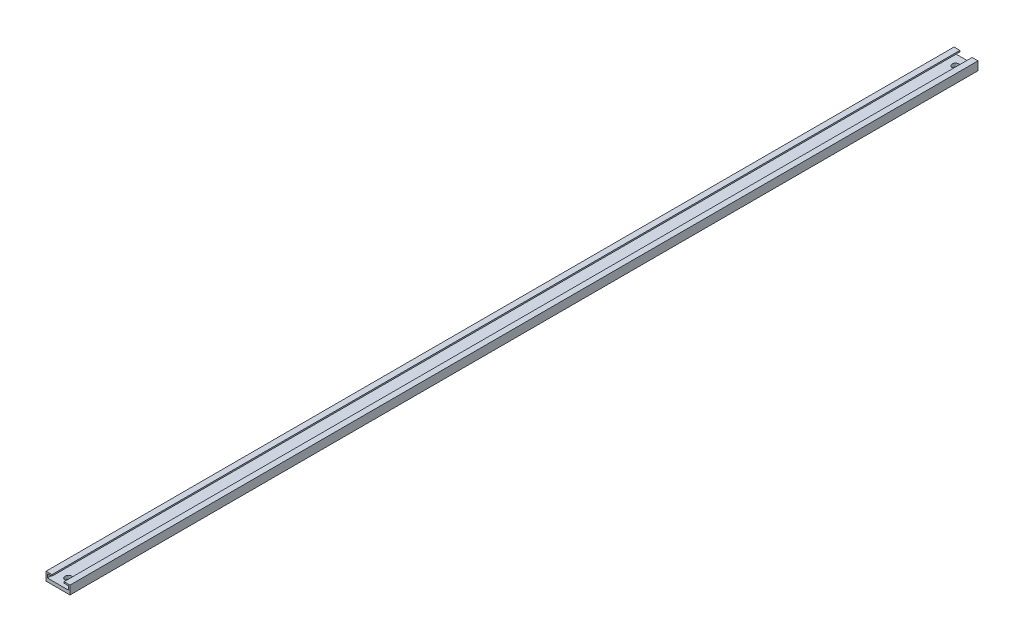
SolidWorks part; units mm, degrees
material "3003 合金"
ref_plane "正面" through (0, 0, 0) normal (0, 0, 1) x (1, 0, 0)
ref_plane "平面" through (0, 0, 0) normal (0, 1, 0) x (1, 0, 0)
ref_plane "右側面" through (0, 0, 0) normal (1, 0, 0) x (0, 0, -1)
sketch "ｽｹｯﾁ1" plane through (0, 0, 0) normal (0, 0, 1) x (1, 0, 0)
  line L0 (-4.4, 3.1) -> (-4.4, 2.1)
  line L1 (8.65, -3.1) -> (-8.65, -3.1)
  line L2 (8.65, -3.1) -> (8.65, 3.1)
  line L3 (8.65, 3.1) -> (4.4, 3.1)
  line L4 (-8.65, -3.1) -> (-8.65, 3.1)
  line L5 (8.65, -3.1) -> (-8.65, 3.1) construction
  line L6 (8.65, 3.1) -> (-8.65, -3.1) construction
  line L7 (7.65, 2.1) -> (4.4, 2.1)
  line L8 (7.65, 2.1) -> (7.65, -0.6)
  line L9 (7.65, -0.6) -> (-7.65, -0.6)
  line L10 (-7.65, 2.1) -> (-7.65, -0.6)
  line L11 (7.65, 2.1) -> (-7.65, -0.6) construction
  line L12 (7.65, -0.6) -> (-7.65, 2.1) construction
  line L13 (4.4, 3.1) -> (4.4, 2.1)
  line L14 (-4.4, 2.6) -> (4.4, 2.6) construction
  line L15 (4.4, 3.1) -> (-4.4, 3.1) construction
  line L16 (-4.4, 3.1) -> (-8.65, 3.1)
  line L17 (4.4, 2.1) -> (-4.4, 2.1) construction
  line L18 (-4.4, 2.1) -> (-7.65, 2.1)
  point P0 (0, 0)
  point P6 (0, 0.75)
  point P17 (0, 2.6)
  dimension "D1" = 8.8
  dimension "D2" = 2.5
  dimension "D3" = 6.2
  dimension "D4" = 17.3
  dimension "D5" = 2.7
  dimension "D6" = 15.3
extrude "ﾎﾞｽ - 押し出し1" add sketch "ｽｹｯﾁ1" along normal blind 655
sketch "ｽｹｯﾁ2" plane through (0, -3.1, 0) normal (0, -1, 0) x (-1, 0, 0)
  line L0 (0, -655) -> (0, -647.5) construction
  line L1 (8.65, -655) -> (-8.65, -655) construction
  circle A0 centre (0, -647.5) radius 2.4
  dimension "D1" = 4.8
  dimension "D2" = 7.5
extrude "ｶｯﾄ - 押し出し1" cut sketch "ｽｹｯﾁ2" against normal up to next
ref_plane "平面1" through (0, 0, 327.5) normal (0, 0, 1) x (1, 0, 0)
mirror "ﾐﾗｰ1" about plane through (0, 0, 327.5) normal (0, 0, 1) of "ｶｯﾄ - 押し出し1"
